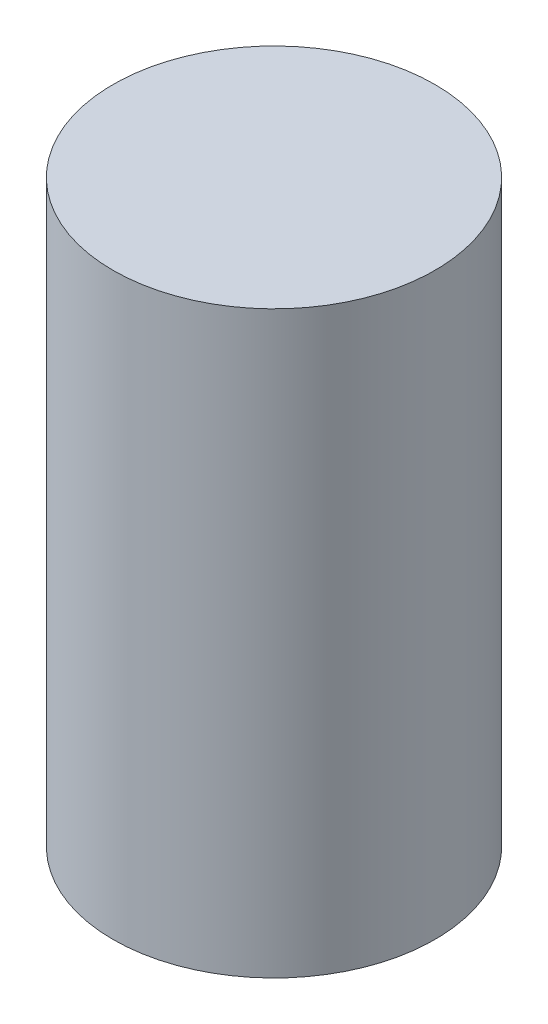
SolidWorks part; units mm, degrees
ref_plane "前视基准面" through (0, 0, 0) normal (0, 0, 1) x (1, 0, 0)
ref_plane "上视基准面" through (0, 0, 0) normal (0, 1, 0) x (1, 0, 0)
ref_plane "右视基准面" through (0, 0, 0) normal (1, 0, 0) x (0, 0, -1)
sketch "草图1" plane through (0, 0, 0) normal (0, 1, 0) x (1, 0, 0)
  circle A0 centre (0, 0) radius 15
  dimension "D1" = 30
extrude "凸台-拉伸1" add sketch "草图1" along normal blind 54
